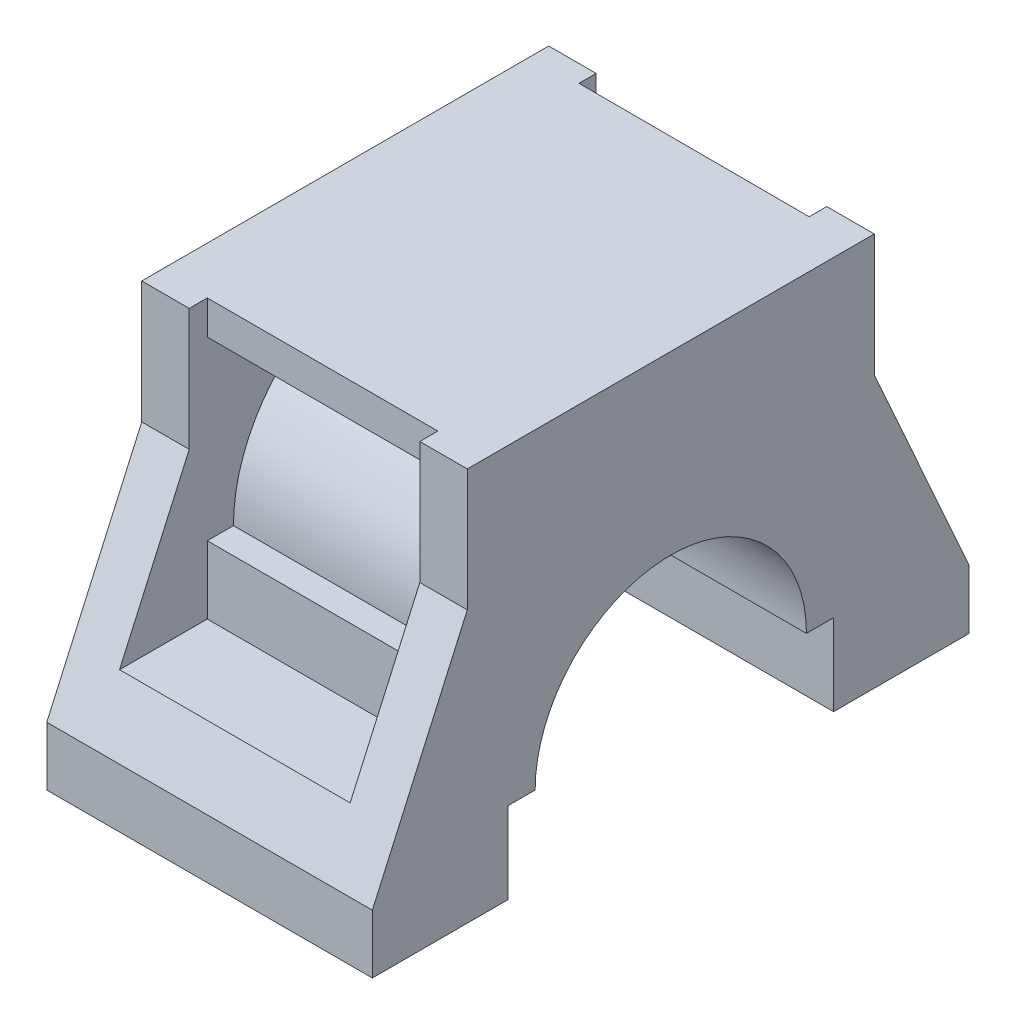
SolidWorks part; units mm, degrees
ref_plane "Front Plane" through (0, 0, 0) normal (0, 0, 1) x (1, 0, 0)
ref_plane "Top Plane" through (0, 0, 0) normal (0, 1, 0) x (1, 0, 0)
ref_plane "Right Plane" through (0, 0, 0) normal (1, 0, 0) x (0, 0, -1)
sketch "Sketch1" plane through (0, 0, 0) normal (1, 0, 0) x (0, 0, -1)
  line L0 (-22.764, 0) -> (-22.764, 8.6591)
  line L1 (-22.764, 8.6591) -> (-8.764, 40)
  line L2 (-8.764, 40) -> (-8.764, 58)
  line L3 (-8.764, 58) -> (51.236, 58)
  line L4 (51.236, 58) -> (51.236, 40)
  line L5 (51.236, 40) -> (65.236, 8.6591)
  line L6 (65.236, 8.6591) -> (65.236, 0)
  line L7 (-22.764, 0) -> (-2.764, 0)
  line L8 (-2.764, 0) -> (-2.764, 12)
  line L9 (-2.764, 12) -> (1.236, 12)
  line L10 (65.236, 0) -> (45.236, 0)
  line L11 (45.236, 0) -> (45.236, 12)
  line L12 (45.236, 12) -> (41.236, 12)
  arc A0 (1.236, 12) -> (41.236, 12) centre (21.236, 12) cw
  dimension "D6" = 20
  dimension "D1" = 88
  dimension "D2" = 48
  dimension "D3" = 58
  dimension "D4" = 40
  dimension "D5" = 12
  dimension "D7" = 60
extrude "Boss-Extrude1" add sketch "Sketch1" against normal blind 48
ref_plane "Plane1" through (-7, 0, 0) normal (1, 0, 0) x (0, 0, -1)
sketch "Sketch2" plane through (-7, 0, 0) normal (1, 0, 0) x (0, 0, -1)
  line L0 (-8.764, 58) -> (1.4164, 58)
  line L1 (51.236, 58) -> (-8.764, 58) construction
sketch "Sketch3" plane through (-7, 0, 0) normal (1, 0, 0) x (0, 0, -1)
  line L0 (-19.0381, 17) -> (-1.0381, 17)
  line L1 (51.236, 58) -> (43.5101, 58)
  line L2 (-8.764, 40) -> (-22.764, 8.6591) construction
  line L3 (51.236, 58) -> (-8.764, 58) construction
  line L4 (-1.0381, 17) -> (-1.0381, 58)
  line L5 (-8.764, 58) -> (1.4164, 58) construction
  line L6 (-1.0381, 58) -> (-8.764, 58)
  line L7 (-8.764, 58) -> (-8.764, 40)
  line L8 (-8.764, 40) -> (-19.0381, 17)
  line L16 (51.236, 58) -> (51.236, 40)
  line L17 (51.236, 40) -> (61.5101, 17)
  line L18 (65.236, 8.6591) -> (51.236, 40) construction
  line L19 (61.5101, 17) -> (43.5101, 17)
  line L20 (43.5101, 17) -> (43.5101, 58)
  dimension "D1" = 23
  dimension "D2" = 18
  dimension "D3" = 18
extrude "Cut-Extrude1" cut sketch "Sketch3" against normal blind 34 contours L8 L0 L4 L6 L7
sketch "Sketch4" plane through (0, 17, 0) normal (0, 1, 0) x (1, 0, 0)
  line L0 (-41, -1.0381) -> (-7, -1.0381)
  line L1 (-7, -8.764) -> (-7, 1.4164) construction
  line L2 (-41, -1.0381) -> (-7, -1.0381) construction
  line L3 (-7, -1.0381) -> (-7, -6.1003)
  line L4 (-7, -31.9) -> (-7, 31.9) construction
  line L5 (-7, -6.1003) -> (-41, -6.1003)
  line L6 (-41, -8.764) -> (-41, -19.0381) construction
  line L7 (-41, -6.1003) -> (-41, -1.0381)
  dimension "D1" = 5.0622
extrude "Boss-Extrude2" add sketch "Sketch4" along normal blind 10
sketch "Sketch5" plane through (0, 0, 0) normal (1, 0, 0) x (0, 0, -1)
  line L0 (51.236, 58) -> (43.2987, 58)
  line L1 (51.236, 58) -> (-8.764, 58) construction
  line L2 (43.2987, 58) -> (43.2987, 17.4733)
  line L3 (43.2987, 17.4733) -> (61.2987, 17.4733)
  line L4 (65.236, 8.6591) -> (51.236, 40) construction
  line L5 (61.2987, 17.4733) -> (51.236, 40)
  line L6 (51.236, 40) -> (51.236, 58)
  dimension "D1" = 18
sketch "Sketch6" plane through (0, 0, 1.0381) normal (0, 0, 1) x (1, 0, 0)
  line L0 (-41, 27) -> (-41, 58)
  line L1 (-41, 58) -> (-7, 58)
  line L2 (-7, -31.9) -> (-7, 31.9) construction
  line L3 (-41, 58) -> (-7, 58) construction
  line L4 (-7, 58) -> (-7, 27)
  line L5 (-7, 27) -> (-41, 27) construction
  line L6 (-7, 27) -> (-41, 27)
extrude "Cut-Extrude3" cut sketch "Sketch6" against normal through all
sketch "Sketch8" plane through (-41, 0, 0) normal (1, 0, 0) x (0, 0, -1)
  line L0 (-2.2461, 27) -> (45.7539, 27)
  line L1 (8.0073, 27) -> (-6.1003, 27) construction
  line L2 (57.0431, 27) -> (34.4648, 27) construction
  arc A0 (-2.2461, 27) -> (45.7539, 27) centre (21.7539, 27) cw
  dimension "D1" = 24
extrude "Boss-Extrude3" add sketch "Sketch8" along normal blind 34
sketch "Sketch9" plane through (0, 27, 0) normal (0, 1, 0) x (1, 0, 0)
  line L9 (-41, 43.5775) -> (-7, 43.5775)
  line L10 (-41, 51.236) -> (-41, -8.764) construction
  line L11 (-7, -31.9) -> (-7, 31.9) construction
  line L12 (-7, 43.5775) -> (-7, 48.6375)
  line L13 (-7, 48.6375) -> (-41, 48.6375)
  line L14 (-41, 48.6375) -> (-41, 43.5775)
  dimension "D1" = 5.06
extrude "Boss-Extrude4" add sketch "Sketch9" along normal blind 10
sketch "Sketch10" plane through (0, 58, 0) normal (0, 1, 0) x (1, 0, 0)
  line L0 (-41, 48.7073) -> (-7, 48.6375)
  line L1 (-41, 51.236) -> (-41, -8.764) construction
  line L2 (-7, -31.9) -> (-7, 31.9) construction
  line L3 (-7, 48.6375) -> (-41, 48.6375) construction
  line L4 (-7, 48.6375) -> (-7, -6.1003)
  line L5 (-7, -8.764) -> (-7, 1.4164) construction
  line L6 (-7, -6.1003) -> (-41, -6.1003)
  line L7 (-41, -6.1003) -> (-41, 48.7073)
extrude "Boss-Extrude5" add sketch "Sketch10" against normal blind 5
